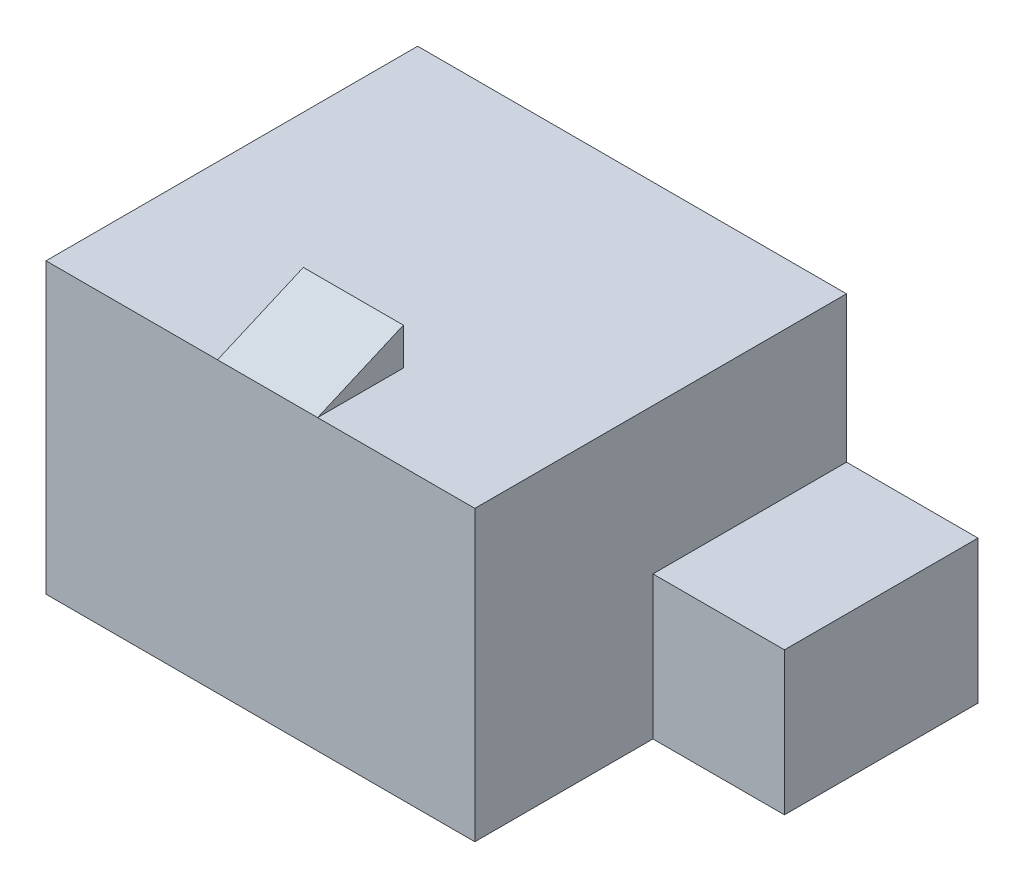
SolidWorks part; units mm, degrees
ref_plane "Front Plane" through (0, 0, 0) normal (0, 0, 1) x (1, 0, 0)
ref_plane "Top Plane" through (0, 0, 0) normal (0, 1, 0) x (1, 0, 0)
ref_plane "Right Plane" through (0, 0, 0) normal (1, 0, 0) x (0, 0, -1)
sketch "Sketch1" plane through (0, 0, 0) normal (0, 1, 0) x (1, 0, 0)
  line L1 (0, 0) -> (15, 0)
  line L2 (0, 0) -> (0, 13)
  line L3 (0, 13) -> (15, 13)
  line L4 (15, 0) -> (15, 13)
extrude "Boss-Extrude1" add sketch "Sketch1" along normal blind 10.1
sketch "Sketch2" plane through (0, 10.1, 0) normal (0, 1, 0) x (1, 0, 0)
  line L0 (0, 0) -> (15, 0) construction
  line L1 (6, 3) -> (9.5, 3)
  line L2 (6, 3) -> (6, 0)
  line L3 (6, 0) -> (9.5, 0)
  line L4 (9.5, 3) -> (9.5, 0)
extrude "Boss-Extrude2" add sketch "Sketch2" along normal blind 1.3
sketch "Sketch3" plane through (9.5, 0, 0) normal (1, 0, 0) x (0, 0, -1)
  line L0 (0, 10.1) -> (3, 11.4)
  line L1 (3, 11.4) -> (0, 11.4)
  line L2 (0, 11.4) -> (0, 10.1)
extrude "Cut-Extrude1" cut sketch "Sketch3" against normal up to next
sketch "Sketch4" plane through (15, 0, 0) normal (1, 0, 0) x (0, 0, -1)
  line L1 (13, 0) -> (6.23, 0)
  line L2 (13, 0) -> (13, 5)
  line L3 (13, 5) -> (6.23, 5)
  line L4 (6.23, 0) -> (6.23, 5)
extrude "Boss-Extrude3" add sketch "Sketch4" along normal blind 4.6
sketch "Sketch5" plane through (0, 0, 0) normal (-1, 0, 0) x (0, 0, 1)
  line L5 (-6.23, 5) -> (-13, 5)
  line L6 (-6.23, 5) -> (-6.23, 0)
  line L7 (-6.23, 0) -> (-13, 0)
  line L8 (-13, 5) -> (-13, 0)
extrude "Boss-Extrude4" add sketch "Sketch5" along normal blind 4.6
